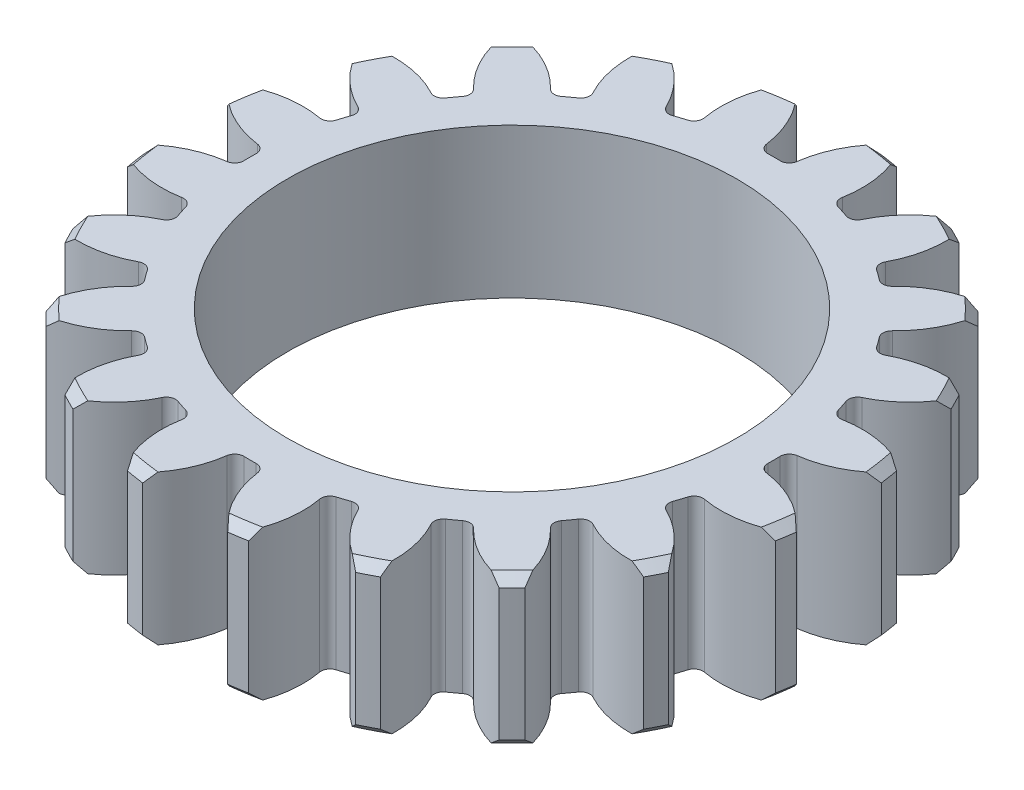
SolidWorks part; units mm, degrees
ref_plane "Front Plane" through (0, 0, 0) normal (0, 0, 1) x (1, 0, 0)
ref_plane "Top Plane" through (0, 0, 0) normal (0, 1, 0) x (1, 0, 0)
ref_plane "Right Plane" through (0, 0, 0) normal (1, 0, 0) x (0, 0, -1)
sketch "Sketch1" plane through (0, 0, 0) normal (0, 1, 0) x (1, 0, 0)
  circle A0 centre (0, 0) radius 20
  circle A1 centre (0, 0) radius 22
  circle A2 centre (0, 0) radius 17.5
  dimension "D1" = 40
  dimension "addendum" = 2
  dimension "dedendum" = 2.5
extrude "Boss-Extrude1" add sketch "Sketch1" along normal blind 10 contours A1
sketch "Sketch2" plane through (0, 0, 0) normal (0, -1, 0) x (1, 0, 0)
  line L0 (0, 0) -> (0, 41.9432) construction
  line L1 (-0.9626, 17.4735) -> (0, 0) construction
  line L2 (0.9626, 17.4735) -> (0, 0) construction
  line L3 (-1.5692, 19.9383) -> (1.5692, 19.9383) construction
  line L4 (-5.0152, 27.5) -> (-4.0305, 25.3393) construction
  line L5 (-1.5692, 19.9383) -> (4.5196, 22.7132) construction
  line L6 (-1.5692, 19.9383) -> (1.8919, 20.2107) construction
  line L7 (0, 0) -> (6.5686, 41.4726) construction
  line L8 (1.5692, 19.9383) -> (4.6689, 19.4474) construction
  arc A0 (-2.8367, 21.8164) -> (-0.9626, 17.4735) centre (-7.8048, 17.0966) cw
  circle A1 centre (0, 0) radius 22 construction
  circle A2 centre (0, 0) radius 17.5 construction
  arc A3 (2.8367, 21.8164) -> (0.9626, 17.4735) centre (7.8048, 17.0966) ccw
  circle A4 centre (0, 0) radius 20 construction
  arc A5 (0.9626, 17.4735) -> (-0.9626, 17.4735) centre (0, 0) ccw
  arc A6 (2.8367, 21.8164) -> (-2.8367, 21.8164) centre (0, 0) ccw
  point P13 (-1.5692, 19.9383)
  point P14 (1.5692, 19.9383)
  dimension "D1" = 20
  dimension "D2" = 9
extrude "Cut-Extrude1" cut sketch "Sketch2" against normal up to surface (10 mm away) up to face at (0, 10, 22)
fillet "Fillet1" radius 0.6 2 edges at (0.9626, 5, 17.4735) (-0.9626, 5, 17.4735)
chamfer "Chamfer1" distance 0.6 angle 45 2 edges at (0, 0, -22) (0, 10, -22)
pattern_circular "CirPattern1" count 20 over 360 about axis through (0, 0, 0) along (0, 1, 0) of "Cut-Extrude1", "Fillet1"
sketch "Sketch3" plane through (0, 0, 0) normal (0, -1, 0) x (1, 0, 0)
  circle A0 centre (0, 0) radius 15
  dimension "D1" = 30
extrude "Cut-Extrude2" cut sketch "Sketch3" against normal up to surface (10 mm away) up to face at (0, 10, 0)
equation "\"module\"= 2mm"
equation "\"noTeeth\"= 20"
equation "\"pressureAngle\"= 20deg"
equation "\"width\"= 10mm"
equation "\"D1@Sketch1\"=\"module\"*\"noTeeth\""
equation "\"dedendum@Sketch1\" = \"module\" * 1.25"
equation "\"addendum@Sketch1\" = \"module\""
equation "\"D1@Sketch2\"=\"pressureAngle\""
equation "\"D2@Sketch2\"=180/\"noTeeth\""
equation "\"D1@Fillet1\"=0.3*\"module\""
equation "\"D1@Chamfer1\"=0.3*\"module\""
equation "\"D1@CirPattern1\"=\"noTeeth\""
